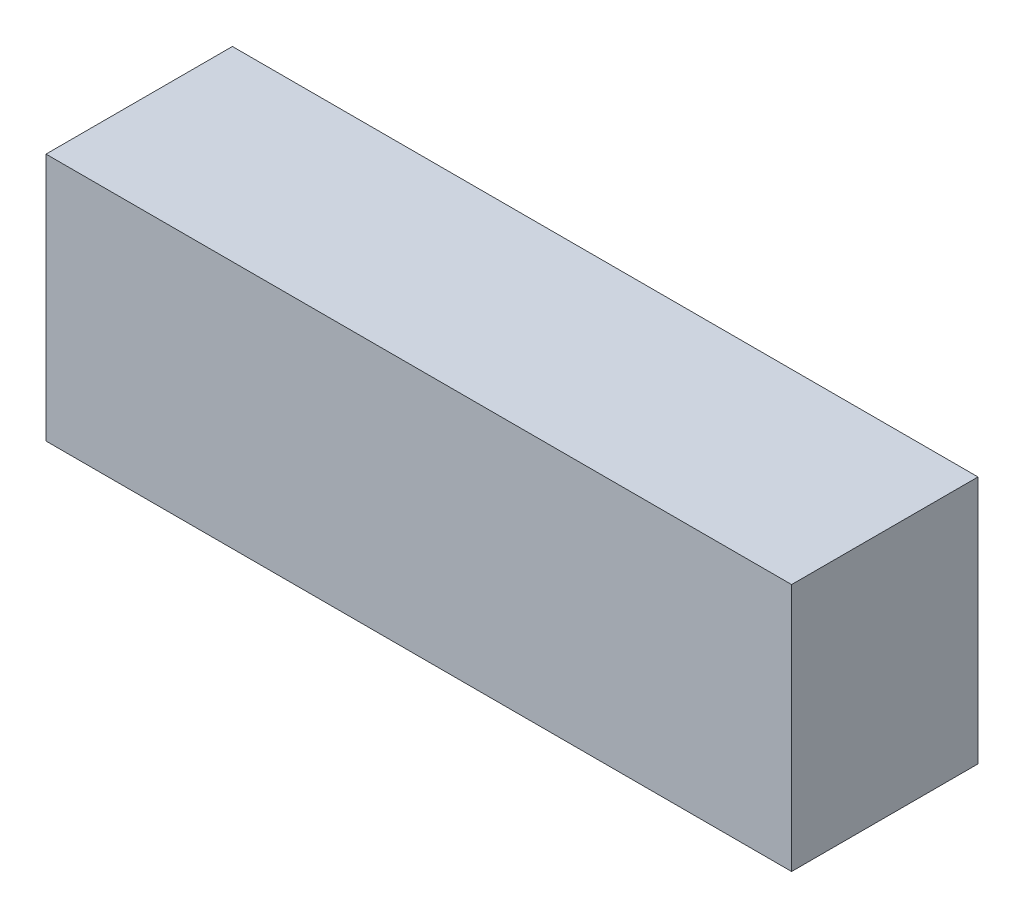
SolidWorks part; units mm, degrees
material "Custom Plastic"
ref_plane "X-Y Datum" through (0, 0, 0) normal (0, 0, 1) x (1, 0, 0)
ref_plane "X-Z Datum" through (0, 0, 0) normal (0, 1, 0) x (1, 0, 0)
ref_plane "Y-Z Datum" through (0, 0, 0) normal (1, 0, 0) x (0, 0, -1)
sketch "Sketch1" plane through (0, 0, 0) normal (0, 0, 1) x (1, 0, 0)
  line L1 (-19.05, 6.35) -> (19.05, 6.35)
  line L2 (-19.05, 6.35) -> (-19.05, -6.35)
  line L3 (-19.05, -6.35) -> (19.05, -6.35)
  line L4 (19.05, 6.35) -> (19.05, -6.35)
  line L5 (-19.05, 6.35) -> (19.05, -6.35) construction
  line L6 (-19.05, -6.35) -> (19.05, 6.35) construction
  point P0 (0, 0)
  dimension "D1" = 38.1
  dimension "D2" = 12.7
extrude "Boss-Extrude1" add sketch "Sketch1" along normal blind 9.525
